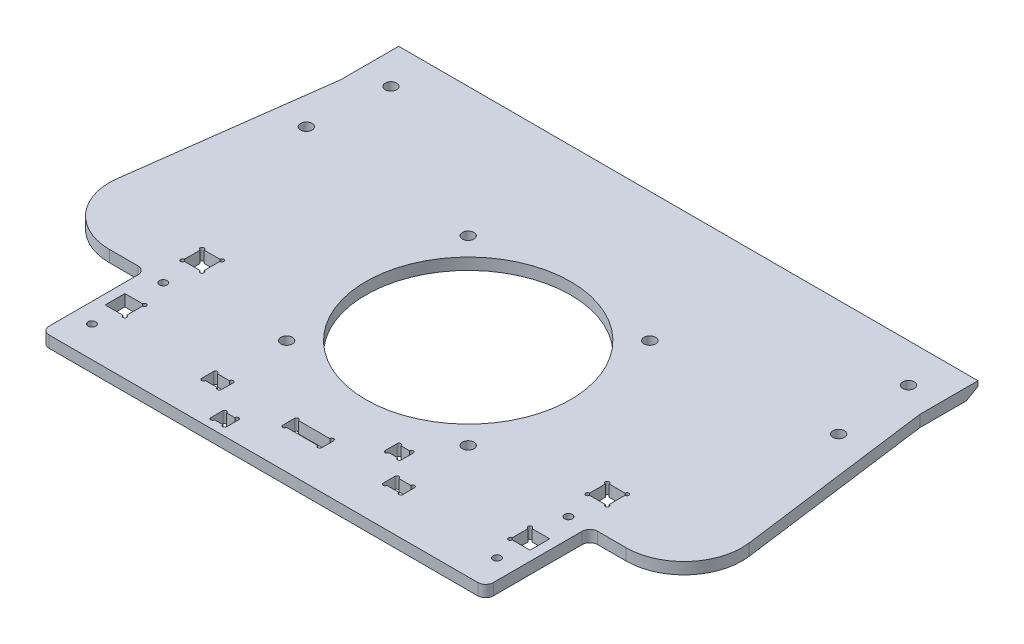
SolidWorks part; units mm, degrees
ref_plane "Front Plane" through (0, 0, 0) normal (0, 0, 1) x (1, 0, 0)
ref_plane "Top Plane" through (0, 0, 0) normal (0, 1, 0) x (1, 0, 0)
ref_plane "Right Plane" through (0, 0, 0) normal (1, 0, 0) x (0, 0, -1)
sketch "Sketch1" plane through (0, 0, 0) normal (0, 1, 0) x (1, 0, 0)
  line L0 (75, 95) -> (75, 110)
  line L1 (57.5, 27) -> (57.5, 19.1)
  line L2 (57.5, 27) -> (84, 27)
  line L3 (75, 95) -> (84, 27)
  line L4 (75, 110) -> (-75, 110)
  line L5 (0, 110) -> (0, 0) construction
  line L6 (57.5, 0) -> (-57.5, 0)
  line L7 (-57.5, 14) -> (-55, 14) construction
  line L8 (-57.5, 27) -> (-84, 27)
  line L9 (-75, 95) -> (-75, 110)
  line L10 (-75, 95) -> (-84, 27)
  line L11 (55, 19.1) -> (49.9, 19.1)
  line L12 (49.9, 19.1) -> (49.9, 14)
  line L13 (49.9, 14) -> (55, 14)
  line L14 (57.5, 14) -> (57.5, 0)
  line L15 (-57.5, 19.1) -> (-55, 19.1) construction
  line L16 (55, 34) -> (49.9, 34)
  line L17 (55, 34) -> (55, 39.1)
  line L18 (55, 39.1) -> (49.9, 39.1)
  line L19 (49.9, 34) -> (49.9, 39.1)
  line L20 (-55, 19.1) -> (-55, 14)
  line L21 (-57.5, 19.1) -> (-57.5, 14)
  line L22 (-49.9, 34) -> (-49.9, 39.1)
  line L23 (-55, 39.1) -> (-49.9, 39.1)
  line L24 (-55, 34) -> (-55, 39.1)
  line L25 (-55, 34) -> (-49.9, 34)
  line L26 (-57.5, 14) -> (-57.5, 0)
  line L27 (57.5, 19.1) -> (57.5, 14)
  line L28 (55, 19.1) -> (55, 14)
  line L29 (57.5, 19.1) -> (55, 19.1) construction
  line L30 (57.5, 14) -> (55, 14) construction
  line L31 (-49.9, 14) -> (-55, 14)
  line L32 (-49.9, 19.1) -> (-49.9, 14)
  line L33 (-55, 19.1) -> (-49.9, 19.1)
  line L34 (-57.5, 27) -> (-57.5, 19.1)
  dimension "D1" = 5.1
  dimension "D2" = 75
  dimension "D3" = 15
  dimension "D4" = 57.5
  dimension "D5" = 26.5
  dimension "D6" = 110
  dimension "D7" = 27
  dimension "D8" = 5.1
  dimension "D9" = 7
  dimension "D10" = 14
  dimension "D11" = 172.461
  dimension "D12" = 2.5
extrude "Boss-Extrude1" add sketch "Sketch1" along normal blind 3
sketch "Sketch2" plane through (0, 3, 0) normal (0, 1, 0) x (1, 0, 0)
  line L0 (0, 110) -> (0, 0) construction
  line L1 (75, 110) -> (-75, 110) construction
  line L2 (23.5113, 76.5113) -> (-23.5113, 29.4887) construction
  line L3 (-23.5113, 76.5113) -> (23.5113, 29.4887) construction
  line L4 (-4.9811, 53) -> (4.9811, 53) construction
  circle A0 centre (0, 53) radius 26.5
  circle A1 centre (23.5113, 76.5113) radius 1.5
  circle A2 centre (-23.5113, 76.5113) radius 1.5
  circle A3 centre (-23.5113, 29.4887) radius 1.5
  circle A4 centre (23.5113, 29.4887) radius 1.5
  dimension "D1" = 53
  dimension "D5" = 3
  dimension "D2" = 90
  dimension "D3" = 45
  dimension "D4" = 66.5
  dimension "D6" = 57
extrude "Cut-Extrude1" cut sketch "Sketch2" against normal blind 3
fillet "Fillet1" radius 15 2 edges at (84, 1.5, -27) (-84, 1.5, -27)
sketch "Sketch7" plane through (0, 0, 0) normal (0, -1, 0) x (1, 0, 0)
  line L0 (-16.05, -2.4) -> (-11.95, -2.4)
  line L1 (-16.05, -2.4) -> (-16.05, -5.5)
  line L2 (-16.05, -5.5) -> (-11.95, -5.5)
  line L3 (-11.95, -2.4) -> (-11.95, -5.5)
  line L4 (13.9, -17.6) -> (18.1, -17.6)
  line L5 (13.9, -17.6) -> (13.9, -20.7)
  line L6 (13.9, -20.7) -> (18.1, -20.7)
  line L7 (18.1, -17.6) -> (18.1, -20.7)
  line L8 (-26.05, -10) -> (-20.95, -10)
  line L9 (-26.05, -10) -> (-26.05, -13.1)
  line L10 (-26.05, -13.1) -> (-20.95, -13.1)
  line L11 (-20.95, -10) -> (-20.95, -13.1)
  line L12 (20.95, -10) -> (26.05, -10)
  line L13 (20.95, -10) -> (20.95, -13.1)
  line L14 (20.95, -13.1) -> (26.05, -13.1)
  line L15 (26.05, -10) -> (26.05, -13.1)
  line L16 (-5.05, -10) -> (5.05, -10)
  line L17 (-5.05, -10) -> (-5.05, -13.1)
  line L18 (-5.05, -13.1) -> (5.05, -13.1)
  line L19 (5.05, -10) -> (5.05, -13.1)
  line L20 (-55, 0) -> (55, 0) construction
  line L21 (-55, 0) -> (-55, -39) construction
  line L22 (-55, -39) -> (55, -39) construction
  line L23 (55, 0) -> (55, -39) construction
  line L24 (0, 0) -> (0, -39) construction
  line L25 (-14, -2.4) -> (-14, -5.5) construction
  line L26 (-23.5, -10) -> (-23.5, -13.1) construction
  line L27 (0, -10) -> (0, -13.1) construction
  line L28 (23.5, -10) -> (23.5, -13.1) construction
  line L29 (16, -17.6) -> (16, -20.7) construction
  dimension "D1" = 14
  dimension "D2" = 23.5
  dimension "D3" = 23.5
  dimension "D4" = 16
  dimension "D5" = 2.4
  dimension "D6" = 10
  dimension "D7" = 10
  dimension "D8" = 10
  dimension "D9" = 17.6
  dimension "D10" = 10.1
  dimension "D11" = 5.1
  dimension "D12" = 110
  dimension "D13" = 39
  dimension "D14" = 4.2
  dimension "D15" = 5.1
  dimension "D16" = 4.1
  dimension "D17" = 3.1
extrude "Cut-Extrude4" cut sketch "Sketch7" against normal blind 10
sketch "Sketch4" plane through (0, 3, 0) normal (0, 1, 0) x (1, 0, 0)
  line L0 (55, 39.1) -> (49.9, 39.1) construction
  line L1 (55, 34) -> (55, 39.1) construction
  line L2 (49.9, 39.1) -> (49.9, 34) construction
  line L3 (49.9, 34) -> (55, 34) construction
  line L4 (49.9, 19.1) -> (55, 19.1) construction
  line L5 (49.9, 14) -> (49.9, 19.1) construction
  line L6 (0, 0) -> (0, 22.5564) construction
  line L7 (55, 14) -> (49.9, 14) construction
  line L8 (-5.05, 13.1) -> (5.05, 13.1) construction
  line L9 (5.05, 10) -> (-5.05, 10) construction
  line L14 (13.9, 20.7) -> (18.1, 20.7) construction
  line L15 (18.1, 17.6) -> (13.9, 17.6) construction
  line L16 (20.95, 13.1) -> (26.05, 13.1) construction
  line L17 (26.05, 10) -> (20.95, 10) construction
  line L18 (50.4, 39.1) -> (49.9, 39.1)
  line L19 (49.9, 39.1) -> (49.9, 38.6)
  line L20 (54.5, 39.1) -> (55, 39.1)
  line L21 (55, 39.1) -> (55, 38.6)
  line L22 (55, 34.5) -> (55, 34)
  line L23 (55, 34) -> (54.5, 34)
  line L24 (49.9, 34.5) -> (49.9, 34)
  line L25 (49.9, 34) -> (50.4, 34)
  line L26 (50.4, 34) -> (50.4373, 34.0074)
  line L27 (50.4, 19.1) -> (49.9, 19.1)
  line L28 (49.9, 19.1) -> (49.9, 18.6)
  line L29 (49.9, 18.6) -> (49.9737, 13.5816)
  line L30 (49.9, 14.5) -> (49.9, 14)
  line L31 (49.9, 14) -> (50.4, 14)
  line L32 (25.05, 13.1) -> (26.05, 13.1)
  line L33 (20.95, 13.1) -> (21.95, 13.1)
  line L34 (20.95, 10) -> (21.95, 10)
  line L35 (25.05, 10) -> (26.05, 10)
  line L36 (13.9, 20.7) -> (14.9, 20.7)
  line L37 (17.1, 20.7) -> (18.1, 20.7)
  line L38 (18.1, 17.6) -> (17.1, 17.6)
  line L39 (13.9, 17.6) -> (14.9, 17.6)
  line L40 (4.05, 13.1) -> (5.05, 13.1)
  line L41 (5.05, 10) -> (4.05, 10)
  line L42 (-5.05, 10) -> (-4.05, 10)
  line L43 (-4.05, 13.1) -> (-5.05, 13.1)
  line L44 (-16.05, 5.5) -> (-15.05, 5.5)
  line L45 (-12.95, 5.5) -> (-11.95, 5.5)
  line L46 (-11.95, 2.4) -> (-12.95, 2.4)
  line L47 (-16.05, 2.4) -> (-15.05, 2.4)
  line L48 (-25.05, 10) -> (-26.05, 10)
  line L49 (-20.95, 10) -> (-21.95, 10)
  line L50 (-20.95, 13.1) -> (-21.95, 13.1)
  line L51 (-25.05, 13.1) -> (-26.05, 13.1)
  line L52 (-49.9, 14) -> (-50.4, 14)
  line L53 (-49.9, 14.5) -> (-49.9, 14)
  line L54 (-49.9, 18.6) -> (-49.9737, 13.5816)
  line L55 (-49.9, 19.1) -> (-49.9, 18.6)
  line L56 (-50.4, 19.1) -> (-49.9, 19.1)
  line L57 (-50.4, 34) -> (-50.4373, 34.0074)
  line L58 (-49.9, 34) -> (-50.4, 34)
  line L59 (-49.9, 34.5) -> (-49.9, 34)
  line L60 (-55, 34) -> (-54.5, 34)
  line L61 (-55, 34.5) -> (-55, 34)
  line L62 (-55, 39.1) -> (-55, 38.6)
  line L63 (-54.5, 39.1) -> (-55, 39.1)
  line L64 (-49.9, 39.1) -> (-49.9, 38.6)
  line L65 (-50.4, 39.1) -> (-49.9, 39.1)
  arc A0 (54.5, 39.1) -> (55, 38.6) centre (55, 39.1) cw
  arc A1 (50.4, 39.1) -> (49.9, 38.6) centre (49.9, 39.1) ccw
  arc A2 (49.9, 34.5) -> (50.4, 34) centre (49.9, 34) ccw
  arc A3 (55, 34.5) -> (54.5, 34) centre (55, 34) cw
  arc A4 (50.4, 19.1) -> (49.9, 18.6) centre (49.9, 19.1) ccw
  arc A5 (49.9, 14.5) -> (50.4, 14) centre (49.9, 14) ccw
  arc A6 (-20.95, 10) -> (-21.95, 10) centre (-21.45, 10) cw
  arc A7 (-26.05, 10) -> (-25.05, 10) centre (-25.55, 10) ccw
  arc A8 (-26.05, 13.1) -> (-25.05, 13.1) centre (-25.55, 13.1) cw
  arc A9 (-20.95, 13.1) -> (-21.95, 13.1) centre (-21.45, 13.1) ccw
  arc A10 (-11.95, 5.5) -> (-12.95, 5.5) centre (-12.45, 5.5) ccw
  arc A11 (-16.05, 5.5) -> (-15.05, 5.5) centre (-15.55, 5.5) cw
  arc A12 (5.05, 13.1) -> (4.05, 13.1) centre (4.55, 13.1) ccw
  arc A13 (5.05, 10) -> (4.05, 10) centre (4.55, 10) cw
  arc A14 (-16.05, 2.4) -> (-15.05, 2.4) centre (-15.55, 2.4) ccw
  arc A15 (-11.95, 2.4) -> (-12.95, 2.4) centre (-12.45, 2.4) cw
  arc A16 (-5.05, 10) -> (-4.05, 10) centre (-4.55, 10) ccw
  arc A17 (-5.05, 13.1) -> (-4.05, 13.1) centre (-4.55, 13.1) cw
  arc A18 (-49.9, 14.5) -> (-50.4, 14) centre (-49.9, 14) cw
  arc A19 (-50.4, 19.1) -> (-49.9, 18.6) centre (-49.9, 19.1) cw
  arc A20 (-55, 34.5) -> (-54.5, 34) centre (-55, 34) ccw
  arc A21 (-49.9, 34.5) -> (-50.4, 34) centre (-49.9, 34) cw
  arc A22 (-50.4, 39.1) -> (-49.9, 38.6) centre (-49.9, 39.1) cw
  arc A23 (-54.5, 39.1) -> (-55, 38.6) centre (-55, 39.1) ccw
  arc A24 (18.1, 20.7) -> (17.1, 20.7) centre (17.6, 20.7) ccw
  arc A25 (13.9, 20.7) -> (14.9, 20.7) centre (14.4, 20.7) cw
  arc A26 (13.9, 17.6) -> (14.9, 17.6) centre (14.4, 17.6) ccw
  arc A27 (18.1, 17.6) -> (17.1, 17.6) centre (17.6, 17.6) cw
  arc A28 (20.95, 13.1) -> (21.95, 13.1) centre (21.45, 13.1) cw
  arc A29 (26.05, 13.1) -> (25.05, 13.1) centre (25.55, 13.1) ccw
  arc A30 (26.05, 10) -> (25.05, 10) centre (25.55, 10) cw
  arc A31 (20.95, 10) -> (21.95, 10) centre (21.45, 10) ccw
  dimension "D1" = 0.5
chamfer "Chamfer1" distance 3 angle 30 1 edges at (0, 0, -110)
extrude "Cut-Extrude5" cut sketch "Sketch4" against normal blind 10 contours L18 A1 L19 | A0 L20 L21 | A3 L22 L23 | L24 A2 L25 | L28 L27 A4 | A5 L31 L30 | A25 L36 | A24 L37 | A27 L38 | A26 L39 | A28 L33 | A29 L32 | A30 L35 | A31 L34 | A12 L40 | A13 L41 | A17 L43 | A16 L42 | A10 L45 | A15 L46 | A14 L47 | A11 L44 | A6 L49 | A9 L50 | A8 L51 | A7 L48 | L55 L56 A19 | A18 L52 L53 | A22 L64 L65 | L58 L59 A21 | A23 L62 L63 | A20 L60 L61
sketch "Sketch9" plane through (0, 3, 0) normal (0, 1, 0) x (1, 0, 0)
  line L0 (52.45, 34) -> (52.45, 0) construction
  line L1 (50.4, 34) -> (54.5, 34) construction
  line L2 (-57.5, 0) -> (57.5, 0) construction
  line L3 (55, 14) -> (50.4, 14) construction
  line L4 (0, 110) -> (0, 0) construction
  line L5 (75, 110) -> (-75, 110) construction
  line L6 (75, 95) -> (75, 110) construction
  line L7 (81.7542, 43.9681) -> (75, 95) construction
  circle A0 centre (52.45, 26.5) radius 1
  circle A1 centre (52.45, 8) radius 1
  circle A2 centre (67, 100) radius 1.5
  circle A3 centre (68.9155, 80) radius 1.5
  circle A4 centre (-52.45, 8) radius 1
  circle A5 centre (-52.45, 26.5) radius 1
  circle A6 centre (-68.9155, 80) radius 1.5
  circle A7 centre (-67, 100) radius 1.5
  dimension "D1" = 2
  dimension "D4" = 3
  dimension "D5" = 10
  dimension "D2" = 7.5
  dimension "D3" = 6
  dimension "D6" = 8
  dimension "D7" = 15
  dimension "D8" = 8
  dimension "D9" = 5
extrude "Cut-Extrude6" cut sketch "Sketch9" against normal blind 10
fillet "Fillet3" radius 2 4 edges at (-57.5, 1.5, -27) (-57.5, 1.5, 0) (57.5, 1.5, 0) (57.5, 1.5, -27)
